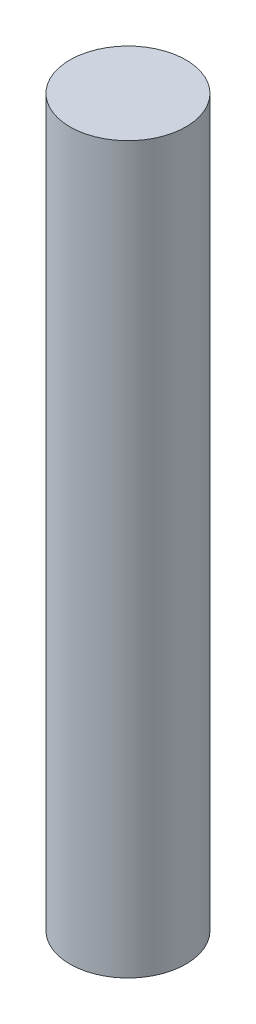
SolidWorks part; units mm, degrees
ref_plane "Front Plane" through (0, 0, 0) normal (0, 0, 1) x (1, 0, 0)
ref_plane "Top Plane" through (0, 0, 0) normal (0, 1, 0) x (1, 0, 0)
ref_plane "Right Plane" through (0, 0, 0) normal (1, 0, 0) x (0, 0, -1)
sketch "Sketch1" plane through (0, 0, 0) normal (0, 1, 0) x (1, 0, 0)
  circle A0 centre (0, 0) radius 2.4
  dimension "D1" = 4.8
extrude "Boss-Extrude1" add sketch "Sketch1" along normal blind 30
